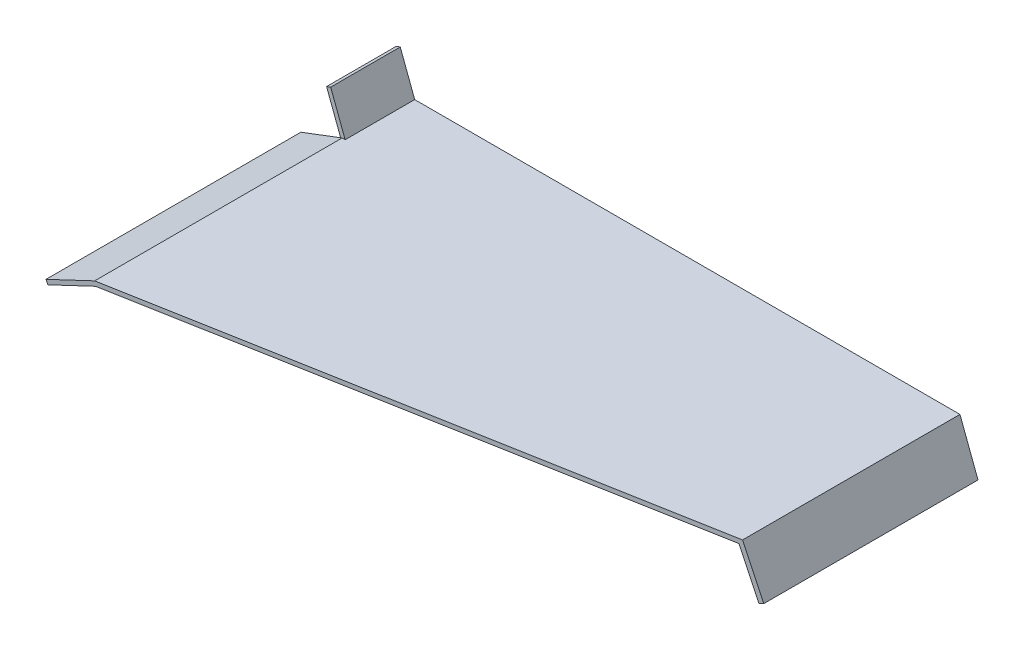
SolidWorks part; units mm, degrees
ref_plane "Front Plane" through (0, 0, 0) normal (0, 0, 1) x (1, 0, 0)
ref_plane "Top Plane" through (0, 0, 0) normal (0, 1, 0) x (1, 0, 0)
ref_plane "Right Plane" through (0, 0, 0) normal (1, 0, 0) x (0, 0, -1)
sketch "Sketch1" plane through (0, 0, 0) normal (0, 1, 0) x (1, 0, 0)
  line L1 (0, 0) -> (395.4099, 0)
  line L2 (0, 0) -> (0, 228.6)
  line L3 (0, 228.6) -> (395.4099, 228.6)
  line L4 (395.4099, 0) -> (395.4099, 228.6)
  dimension "D1" = 228.6
  dimension "D2" = 395.4099
extrude "Boss-Extrude1" add sketch "Sketch1" along normal blind 3.175
sketch "Sketch2" plane through (0, 3.175, 0) normal (0, 1, 0) x (1, 0, 0)
  line L0 (0, 0) -> (395.4099, 71.7959)
  line L1 (395.4099, 0) -> (395.4099, 228.6) construction
  line L2 (395.4099, 71.7959) -> (395.4099, 0)
  line L3 (395.4099, 0) -> (0, 0)
  dimension "D1" = 71.7959
extrude "Cut-Extrude1" cut sketch "Sketch2" against normal blind 3.175
sketch "Sketch3" plane through (0, 0, -228.6) normal (0, 0, -1) x (-1, 0, 0)
  line L0 (-395.4099, 3.175) -> (-408.4108, -31.2841)
  line L1 (-408.4108, -31.2841) -> (-405.4401, -32.4048)
  line L2 (-405.4401, -32.4048) -> (-392.0165, 3.175)
  line L3 (-395.4099, 3.175) -> (0, 3.175) construction
  line L4 (-392.0165, 3.175) -> (-395.4099, 3.175)
  line L5 (-395.4099, 0) -> (0, 0) construction
  dimension "D1" = 36.83
  dimension "D2" = 3.175
  dimension "D3" = 110.671
extrude "Boss-Extrude2" add sketch "Sketch3" against normal up to surface (154.9829 mm away)
sketch "Sketch4" plane through (0, 0, -228.6) normal (0, 0, -1) x (-1, 0, 0)
  line L0 (0, 0) -> (11.2076, 29.7061)
  line L1 (11.2076, 29.7061) -> (8.237, 30.8269)
  line L2 (8.237, 30.8269) -> (-3.3935, 0)
  line L3 (-393.2143, 0) -> (0, 0) construction
  line L4 (-3.3935, 0) -> (0, 0)
  line L5 (-395.4099, 3.175) -> (0, 3.175) construction
  dimension "D1" = 31.75
  dimension "D2" = 3.175
  dimension "D3" = 110.671
extrude "Boss-Extrude3" add sketch "Sketch4" against normal blind 50.165
sketch "Sketch6" plane through (0, 0, -178.435) normal (0, 0, 1) x (1, 0, 0)
  line L0 (0, 3.175) -> (-29.7061, -8.0326)
  line L1 (-29.7061, -8.0326) -> (-28.5853, -11.0032)
  line L2 (-28.5853, -11.0032) -> (8.9944, 3.175)
  line L3 (395.4099, 3.175) -> (0, 3.175) construction
  line L4 (8.9944, 3.175) -> (0, 3.175)
  line L5 (0, 0) -> (-11.2076, 29.7061) construction
  dimension "D1" = 31.75
  dimension "D2" = 3.175
  dimension "D3" = 90
extrude "Boss-Extrude5" add sketch "Sketch6" along normal up to surface (183.6253 mm away)
